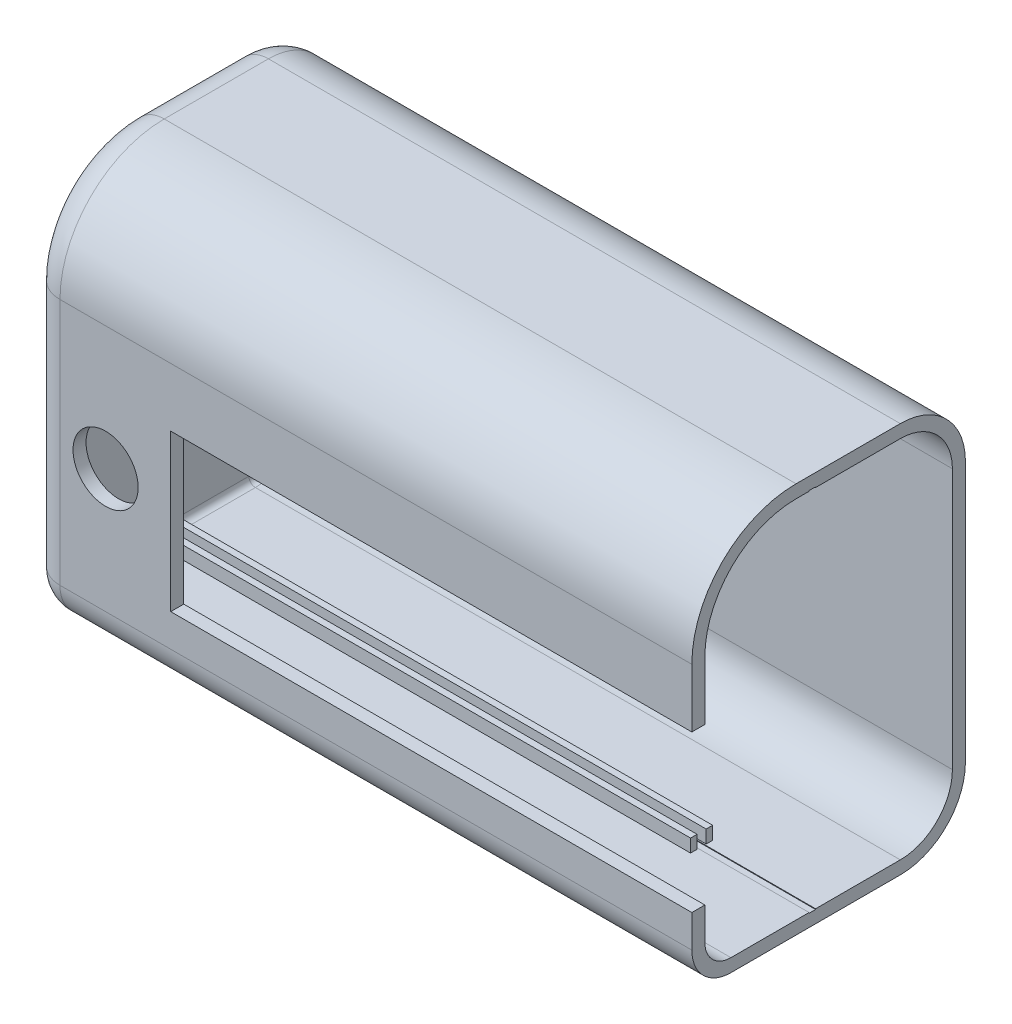
SolidWorks part; units mm, degrees
ref_plane "Спереди" through (0, 0, 0) normal (0, 0, 1) x (1, 0, 0)
ref_plane "Сверху" through (0, 0, 0) normal (0, 1, 0) x (1, 0, 0)
ref_plane "Справа" through (0, 0, 0) normal (1, 0, 0) x (0, 0, -1)
sketch "Эскиз1" plane through (0, 0, 0) normal (1, 0, 0) x (0, 0, -1)
  line L0 (2, 30) -> (40, 30) construction
  line L1 (0, 0) -> (2, 0)
  line L2 (0, 0) -> (0, 60)
  line L3 (0, 60) -> (2, 60)
  line L4 (2, 0) -> (2, 60)
  line L5 (2, 0) -> (18, 0)
  line L6 (2, 0) -> (2, 2)
  line L7 (2, 2) -> (18, 2)
  line L8 (18, 0) -> (18, 2)
  line L9 (18, 0) -> (19, 0)
  line L10 (18, 0) -> (18, 1.9)
  line L11 (18, 1.9) -> (19, 1.9)
  line L12 (19, 0) -> (19, 1.9)
  line L13 (19, 0) -> (40, 0)
  line L14 (19, 0) -> (19, 2)
  line L15 (19, 2) -> (40, 2)
  line L16 (40, 0) -> (40, 2)
  line L17 (2, 60) -> (18, 60)
  line L18 (2, 60) -> (2, 58)
  line L19 (2, 58) -> (18, 58)
  line L20 (18, 60) -> (18, 58)
  line L21 (18, 60) -> (19, 60)
  line L22 (18, 60) -> (18, 58.1)
  line L23 (18, 58.1) -> (19, 58.1)
  line L24 (19, 60) -> (19, 58.1)
  line L25 (19, 60) -> (40, 60)
  line L26 (19, 60) -> (19, 58)
  line L27 (19, 58) -> (40, 58)
  line L28 (40, 60) -> (40, 58)
  line L29 (40, 60) -> (42, 60)
  line L30 (40, 60) -> (40, 0)
  line L31 (40, 0) -> (42, 0)
  line L32 (42, 60) -> (42, 0)
  dimension "D1" = 2
  dimension "D2" = 60
  dimension "D3" = 18
  dimension "D4" = 1.9
  dimension "D5" = 1
  dimension "D6" = 21
extrude "Бобышка-Вытянуть1" add sketch "Эскиз1" against normal blind 90 contours L20 L17 L4 L19 | L24 L21 L20 L23 | L28 L25 L24 L26 L27 | L1 L4 L3 L2 | L32 L29 L28 L30 L16 L31 | L13 L16 L15 L14 L12 | L9 L12 L11 L8 | L5 L8 L7 L4
sketch "Эскиз2" plane through (0, 0, 0) normal (1, 0, 0) x (0, 0, -1)
  line L0 (0, 0) -> (0, 60) construction
  line L1 (0, 11) -> (2, 11)
  line L2 (0, 11) -> (0, 35)
  line L3 (0, 35) -> (2, 35)
  line L4 (2, 11) -> (2, 35)
  line L5 (2, 2) -> (2, 58) construction
  line L7 (0, 0) -> (42, 0) construction
  dimension "D1" = 11
  dimension "D2" = 24
extrude "Вырез-Вытянуть1" cut sketch "Эскиз2" against normal through all
sketch "Эскиз4" plane through (-90, 0, 0) normal (-1, 0, 0) x (0, 0, 1)
  line L1 (-19, 58) -> (-18, 58)
  line L2 (-19, 58) -> (-19, 58.1)
  line L3 (-19, 58.1) -> (-18, 58.1)
  line L4 (-18, 58) -> (-18, 58.1)
  line L5 (-19, 1.9) -> (-18, 1.9)
  line L6 (-19, 1.9) -> (-19, 2)
  line L7 (-19, 2) -> (-18, 2)
  line L8 (-18, 1.9) -> (-18, 2)
extrude "Бобышка-Вытянуть2" add sketch "Эскиз4" against normal blind 3
sketch "Эскиз5" plane through (-90, 0, 0) normal (-1, 0, 0) x (0, 0, 1)
  line L1 (-2, 35) -> (0, 35)
  line L2 (-2, 35) -> (-2, 11)
  line L3 (-2, 11) -> (0, 11)
  line L4 (0, 35) -> (0, 11)
  line M1 (-2, 11) -> (-2, 2)
  line M2 (-2, 2) -> (-40, 2)
  line M3 (-40, 2) -> (-40, 58)
  line M4 (-40, 58) -> (-2, 58)
  line M5 (-2, 58) -> (-2, 35)
  line M6 (-2, 35) -> (0, 35)
  line M7 (0, 35) -> (0, 60)
  line M8 (0, 60) -> (-42, 60)
  line M9 (-42, 60) -> (-42, 0)
  line M10 (-42, 0) -> (0, 0)
  line M11 (0, 0) -> (0, 11)
  line M12 (0, 11) -> (-2, 11)
extrude "Бобышка-Вытянуть3" add sketch "Эскиз5" along normal blind 10 contours M12 M1 M2 M3 M4 M5 M6 M7 M8 M9 M10 M11 | L4 L2 M6 M12
sketch "Эскиз6" plane through (-100, 0, 0) normal (-1, 0, 0) x (0, 0, 1)
  line L4 (-42, 0) -> (0, 0)
  line L5 (0, 0) -> (0, 60)
  line L6 (0, 60) -> (-42, 60)
  line L7 (-42, 60) -> (-42, 0)
  line L8 (-42, 0) -> (0, 0)
  line L9 (0, 0) -> (0, 60)
  line L10 (0, 60) -> (-42, 60)
  line L11 (-42, 60) -> (-42, 0)
  dimension "D1" = 0
extrude "Бобышка-Вытянуть4" add sketch "Эскиз6" along normal blind 2
sketch "Эскиз8" plane through (0, 11, 0) normal (0, 1, 0) x (1, 0, 0)
  line L0 (-90, 2) -> (0, 2) construction
  line L1 (-90, 0) -> (-80, 0)
  line L2 (-90, 0) -> (-90, 2)
  line L3 (-90, 2) -> (-80, 2)
  line L4 (-80, 0) -> (-80, 2)
  dimension "D1" = 10
extrude "Бобышка-Вытянуть5" add sketch "Эскиз8" along normal up to next
sketch "Эскиз7" plane through (0, 0, 0) normal (0, 0, 1) x (1, 0, 0)
  line L0 (-102, 0) -> (-102, 60) construction
  line L1 (-102, 0) -> (0, 0) construction
  circle A0 centre (-90, 25) radius 5
  dimension "D1" = 10
  dimension "D2" = 12
  dimension "D3" = 25
extrude "Вырез-Вытянуть2" cut sketch "Эскиз7" against normal up to next
fillet "Скругление1" radius 14 1 edges at (-50, 58, -2)
fillet "Скругление2" radius 16 1 edges at (-51, 60, 0)
fillet "Скругление4" radius 8 2 edges at (-50, 58, -40) (-50, 2, -40)
fillet "Скругление5" radius 10 2 edges at (-51, 60, -42) (-51, 0, -42)
fillet "Скругление6" radius 4 1 edges at (-50, 2, -2)
fillet "Скругление7" radius 6 1 edges at (-51, 0, 0)
fillet "Скругление8" radius 5 8 edges at (-102, 25, 0) (-102, 1.7574, -1.7574) (-102, 0, -19) (-102, 2.9289, -39.0711) (-102, 30, -42) (-102, 57.0711, -39.0711) (-102, 60, -24) (-102, 55.3137, -4.6863)
fillet "Скругление9" radius 1 8 edges at (-100, 3.1716, -3.1716) (-100, 25, -2) (-100, 53.8995, -6.1005) (-100, 58, -24) (-100, 55.6569, -37.6569) (-100, 30, -40) (-100, 4.3431, -37.6569) (-100, 2, -19)
sketch "Эскиз10" plane through (-87, 0, 0) normal (1, 0, 0) x (0, 0, -1)
  line L0 (19, 58) -> (18, 58) construction
  line L1 (17.8, 58) -> (16.8, 58)
  line L2 (17.8, 58) -> (17.8, 57)
  line L3 (17.8, 57) -> (16.8, 57)
  line L4 (16.8, 58) -> (16.8, 57)
  line L5 (19.2, 58) -> (20.2, 58)
  line L6 (19.2, 58) -> (19.2, 57)
  line L7 (19.2, 57) -> (20.2, 57)
  line L8 (20.2, 58) -> (20.2, 57)
  line L9 (19, 58.1) -> (19, 58) construction
  dimension "D1" = 0.2
  dimension "D2" = 0.2
  dimension "D3" = 1
extrude "Бобышка-Вытянуть6" add sketch "Эскиз10" against normal up to next and the other way blind 20
ref_plane "Плоскость1" through (0, 30, 0) normal (0, -1, 0) x (-1, 0, 0)
mirror "Зеркальное отражение1" about plane through (0, 30, 0) normal (0, -1, 0) of "Бобышка-Вытянуть6"
sketch "Эскиз11" plane through (-67, 0, 0) normal (1, 0, 0) x (0, 0, -1)
  line L4 (19.2, 3) -> (19.2, 2)
  line L5 (19.2, 2) -> (20.2, 2)
  line L6 (20.2, 2) -> (20.2, 3)
  line L7 (20.2, 3) -> (19.2, 3)
  line L8 (19.2, 3) -> (19.2, 2)
  line L9 (19.2, 2) -> (20.2, 2)
  line L10 (20.2, 2) -> (20.2, 3)
  line L11 (20.2, 3) -> (19.2, 3)
  line L12 (17.8, 2) -> (17.8, 3)
  line L13 (17.8, 3) -> (16.8, 3)
  line L14 (16.8, 3) -> (16.8, 2)
  line L15 (16.8, 2) -> (17.8, 2)
  line L16 (17.8, 2) -> (17.8, 3)
  line L17 (17.8, 3) -> (16.8, 3)
  line L18 (16.8, 3) -> (16.8, 2)
  line L19 (16.8, 2) -> (17.8, 2)
  dimension "D1" = 0
  dimension "D2" = 0
extrude "Бобышка-Вытянуть7" add sketch "Эскиз11" along normal blind 50
sketch "Эскиз12" plane through (0, 57, 0) normal (0, -1, 0) x (1, 0, 0)
  line L4 (-67, -16.8) -> (-100, -16.8)
  line L5 (-100, -16.8) -> (-100, -17.8)
  line L6 (-100, -17.8) -> (-67, -17.8)
  line L7 (-67, -17.8) -> (-67, -16.8)
  line L8 (-67, -16.8) -> (-100, -16.8)
  line L9 (-100, -16.8) -> (-100, -17.8)
  line L10 (-100, -17.8) -> (-67, -17.8)
  line L11 (-67, -17.8) -> (-67, -16.8)
  line L12 (-67, -19.2) -> (-100, -19.2)
  line L13 (-100, -19.2) -> (-100, -20.2)
  line L14 (-100, -20.2) -> (-67, -20.2)
  line L15 (-67, -20.2) -> (-67, -19.2)
  line L16 (-67, -19.2) -> (-100, -19.2)
  line L17 (-100, -19.2) -> (-100, -20.2)
  line L18 (-100, -20.2) -> (-67, -20.2)
  line L19 (-67, -20.2) -> (-67, -19.2)
  dimension "D1" = 0
  dimension "D2" = 0
extrude "Бобышка-Вытянуть8" add sketch "Эскиз12" along normal blind 10
sketch "Эскиз13" plane through (0, 3, 0) normal (0, 1, 0) x (1, 0, 0)
  line L4 (-17, 20.2) -> (-100, 20.2)
  line L5 (-100, 20.2) -> (-100, 19.2)
  line L6 (-100, 19.2) -> (-17, 19.2)
  line L7 (-17, 19.2) -> (-17, 20.2)
  line L8 (-17, 20.2) -> (-100, 20.2)
  line L9 (-100, 20.2) -> (-100, 19.2)
  line L10 (-100, 19.2) -> (-17, 19.2)
  line L11 (-17, 19.2) -> (-17, 20.2)
  line L12 (-17, 17.8) -> (-100, 17.8)
  line L13 (-100, 17.8) -> (-100, 16.8)
  line L14 (-100, 16.8) -> (-17, 16.8)
  line L15 (-17, 16.8) -> (-17, 17.8)
  line L16 (-17, 17.8) -> (-100, 17.8)
  line L17 (-100, 17.8) -> (-100, 16.8)
  line L18 (-100, 16.8) -> (-17, 16.8)
  line L19 (-17, 16.8) -> (-17, 17.8)
  dimension "D1" = 0
  dimension "D2" = 0
extrude "Бобышка-Вытянуть9" add sketch "Эскиз13" along normal blind 1
equation "\"СТЕНКИ\"= 2"
equation "\"D1@Эскиз1\"=\"СТЕНКИ\""
equation "\"D1@Бобышка-Вытянуть4\"=\"СТЕНКИ\""
